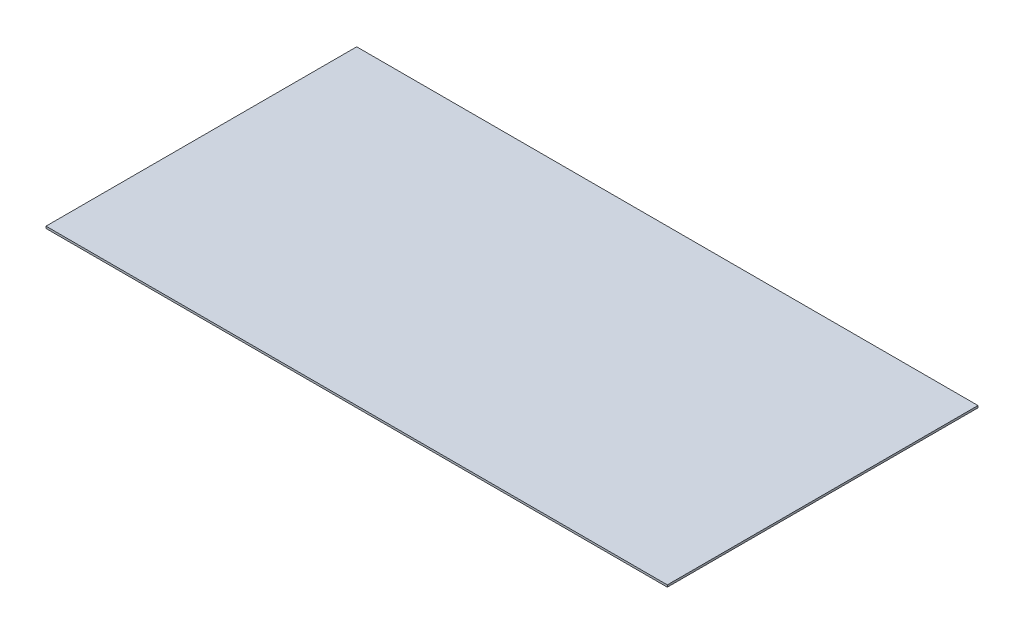
SolidWorks part; units mm, degrees
ref_plane "Front Plane" through (0, 0, 0) normal (0, 0, 1) x (1, 0, 0)
ref_plane "Top Plane" through (0, 0, 0) normal (0, 1, 0) x (1, 0, 0)
ref_plane "Right Plane" through (0, 0, 0) normal (1, 0, 0) x (0, 0, -1)
sketch "Sketch1" plane through (0, 0, 0) normal (0, 1, 0) x (1, 0, 0)
  line L1 (-1219.2, 609.6) -> (1219.2, 609.6)
  line L2 (-1219.2, 609.6) -> (-1219.2, -609.6)
  line L3 (-1219.2, -609.6) -> (1219.2, -609.6)
  line L4 (1219.2, 609.6) -> (1219.2, -609.6)
  line L5 (-1219.2, 609.6) -> (1219.2, -609.6) construction
  line L6 (-1219.2, -609.6) -> (1219.2, 609.6) construction
  point P0 (0, 0)
  dimension "D1" = 2438.4
  dimension "D2" = 1219.2
extrude "Boss-Extrude1" add sketch "Sketch1" along normal blind 8
